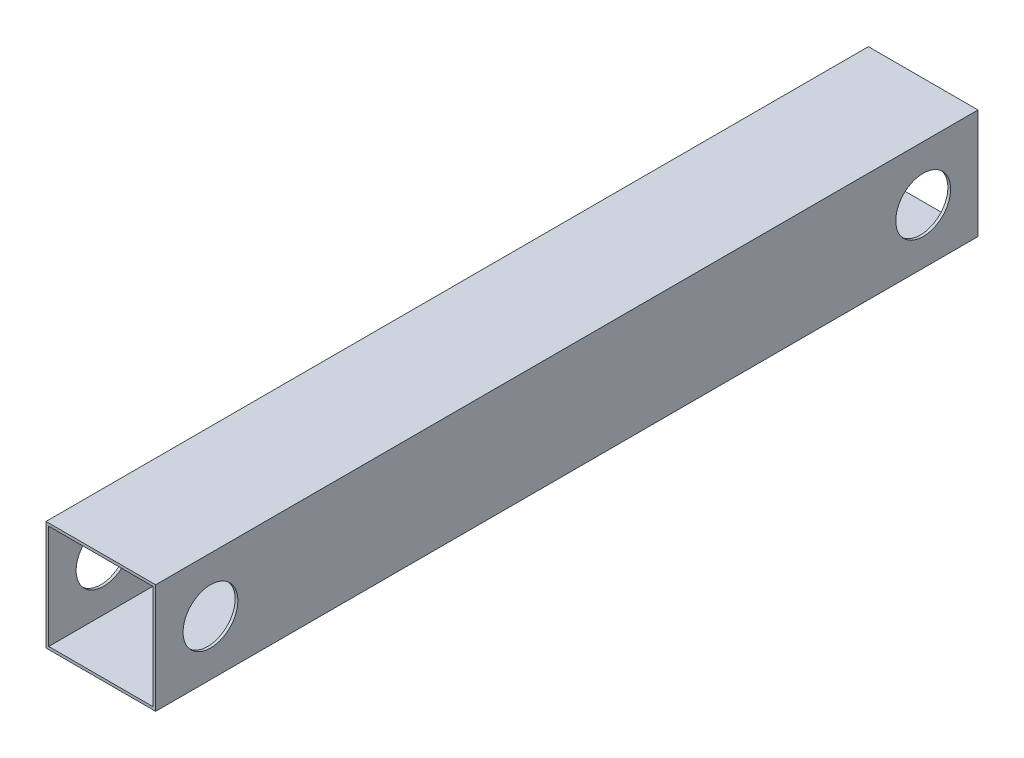
SolidWorks part; units mm, degrees
ref_plane "Front Plane" through (0, 0, 0) normal (0, 0, 1) x (1, 0, 0)
ref_plane "Top Plane" through (0, 0, 0) normal (0, 1, 0) x (1, 0, 0)
ref_plane "Right Plane" through (0, 0, 0) normal (1, 0, 0) x (0, 0, -1)
sketch "Sketch1" plane through (0, 0, 0) normal (0, 0, 1) x (1, 0, 0)
  line L1 (-10, -10) -> (10, -10)
  line L2 (-10, -10) -> (-10, 10)
  line L3 (-10, 10) -> (10, 10)
  line L4 (10, -10) -> (10, 10)
  line L5 (-10, -10) -> (10, 10) construction
  line L6 (-10, 10) -> (10, -10) construction
  line L7 (-9.5, -9.5) -> (9.5, -9.5)
  line L8 (-9.5, -9.5) -> (-9.5, 9.5)
  line L9 (-9.5, 9.5) -> (9.5, 9.5)
  line L10 (9.5, -9.5) -> (9.5, 9.5)
  line L11 (-9.5, -9.5) -> (9.5, 9.5) construction
  line L12 (-9.5, 9.5) -> (9.5, -9.5) construction
  circle A0 centre (0, 0) radius 5 construction
  point P0 (0, 0)
  dimension "D3" = 10
  dimension "D1" = 20
  dimension "D2" = 20
  dimension "D4" = 19
  dimension "D5" = 19
extrude "Boss-Extrude1" add sketch "Sketch1" along normal blind 150
sketch "Sketch2" plane through (10, 0, 0) normal (1, 0, 0) x (0, 0, -1)
  line L0 (-150, 0) -> (0, 0) construction
  line L1 (-150, -10) -> (-150, 10) construction
  line L2 (-75, 10) -> (-75, -10) construction
  line L3 (-150, 10) -> (0, 10) construction
  line L4 (-150, -10) -> (0, -10) construction
  circle A0 centre (-140, 0) radius 5
  circle A1 centre (-10, 0) radius 5
  dimension "D1" = 10
  dimension "D2" = 10
extrude "Cut-Extrude1" cut sketch "Sketch2" against normal blind 150
